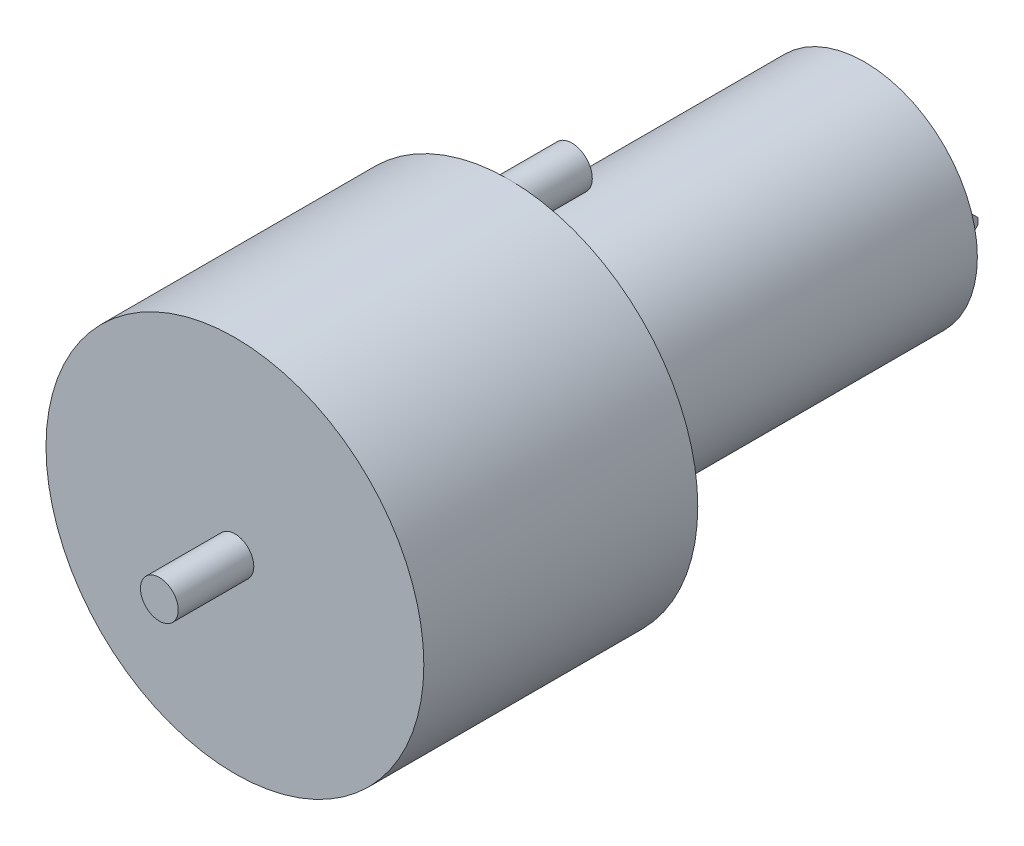
SolidWorks part; units mm, degrees
ref_plane "前视基准面" through (0, 0, 0) normal (0, 0, 1) x (1, 0, 0)
ref_plane "上视基准面" through (0, 0, 0) normal (0, 1, 0) x (1, 0, 0)
ref_plane "右视基准面" through (0, 0, 0) normal (1, 0, 0) x (0, 0, -1)
other "Configuration Table"
sketch "草图4" plane through (0, 0, 0) normal (1, 0, 0) x (0, 0, -1)
  line L0 (0, 0) -> (112, 0)
  line L1 (112, 0) -> (112, 17.9)
  line L2 (112, 17.9) -> (55.5, 17.9)
  line L3 (55.5, 17.9) -> (55.5, 30)
  line L4 (55.5, 30) -> (12, 30)
  line L5 (12, 30) -> (12, 3)
  line L6 (12, 3) -> (0, 3)
  line L7 (0, 3) -> (0, 0)
  dimension "D1" = 3
  dimension "D2" = 12
  dimension "D3" = 112
  dimension "D4" = 43.5
  dimension "D5" = 30
  dimension "D6" = 17.9
revolve "旋转1" add sketch "草图4" angle 360 about L0
sketch "草图5" plane through (0, 0, -55.5) normal (0, 0, -1) x (-1, 0, 0)
  circle A0 centre (0, 26.75) radius 3.25
  circle A1 centre (0, 0) radius 30 construction
  dimension "D1" = 6.5
extrude "凸台-拉伸1" add sketch "草图5" along normal blind 10
sketch "草图7" plane through (0, 0, 0) normal (1, 0, 0) x (0, 0, -1)
  line L0 (112, 0) -> (112, 1.5)
  line L1 (112, -17.9) -> (112, 17.9) construction
  line L2 (112, 1.5) -> (116, 1.5)
  line L3 (116, 1.5) -> (117, 0.5)
  line L4 (117, 0.5) -> (117, -0.5)
  line L5 (117, -0.5) -> (116, -1.5)
  line L6 (116, -1.5) -> (112, -1.5)
  line L7 (112, -1.5) -> (112, 0)
  circle A0 centre (115.5582, 0) radius 0.6773
  point P9 (117, 0)
  dimension "D1" = 3
  dimension "D2" = 1
  dimension "D3" = 5
extrude "凸台-拉伸2" add sketch "草图7" along normal blind 1 from offset 12
mirror "镜向1" about plane through (0, 0, 0) normal (1, 0, 0) of "凸台-拉伸2"
